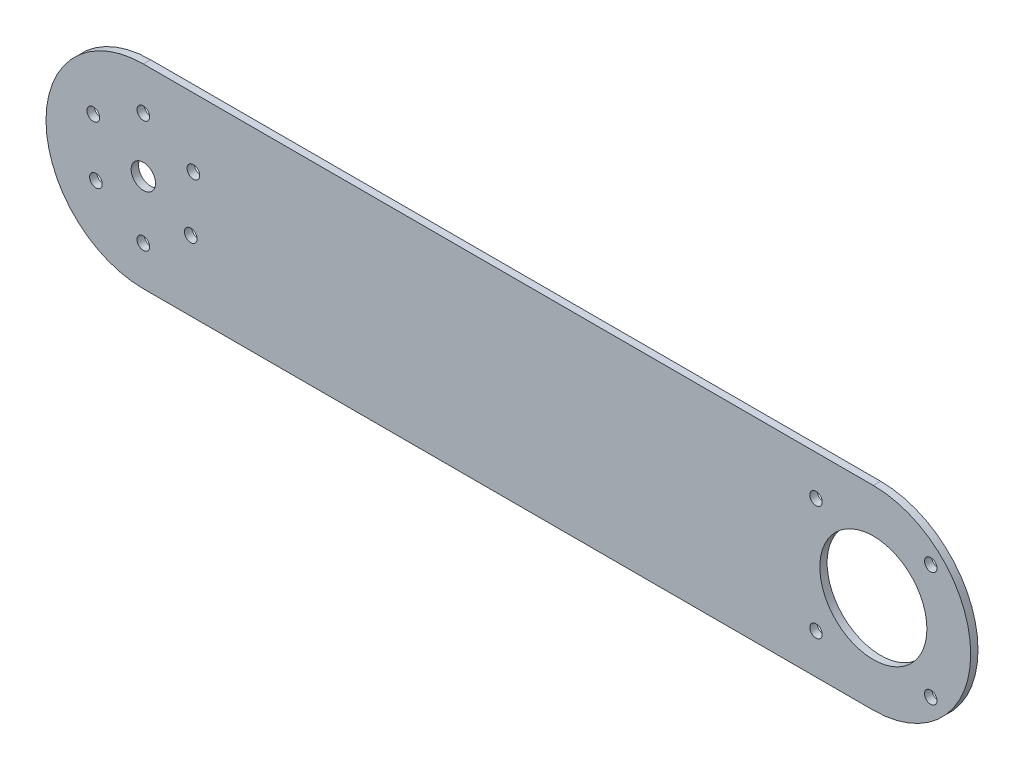
SolidWorks part; units mm, degrees
ref_plane "前视基准面" through (0, 0, 0) normal (0, 0, 1) x (1, 0, 0)
ref_plane "上视基准面" through (0, 0, 0) normal (0, 1, 0) x (1, 0, 0)
ref_plane "右视基准面" through (0, 0, 0) normal (1, 0, 0) x (0, 0, -1)
sketch "草图1" plane through (0, 0, 0) normal (0, 0, 1) x (1, 0, 0)
  line L0 (-3.8235, 4.644) -> (296.1765, 4.644) construction
  line L1 (-3.8235, 4.644) -> (35.4488, -18.03) construction
  line L3 (-3.8235, 44.644) -> (296.1765, 44.644)
  line L4 (-3.8235, -35.356) -> (296.1765, -35.356)
  line L5 (272.6065, 28.214) -> (319.7465, 28.214) construction
  line L6 (272.6065, 28.214) -> (272.6065, -18.926) construction
  line L7 (272.6065, -18.926) -> (319.7465, -18.926) construction
  line L8 (319.7465, 28.214) -> (319.7465, -18.926) construction
  line L9 (272.6065, 28.214) -> (319.7465, -18.926) construction
  line L10 (272.6065, -18.926) -> (319.7465, 28.214) construction
  circle A0 centre (-3.8235, 4.644) radius 23.75 construction
  circle A1 centre (-3.8235, 4.644) radius 22.5 construction
  circle A2 centre (-3.8235, -19.106) radius 2.6
  circle A5 centre (15.662, -6.606) radius 2.6
  circle A16 centre (-3.8235, 4.644) radius 40 construction
  circle A17 centre (296.1765, 4.644) radius 40 construction
  arc A18 (-3.8235, 44.644) -> (-3.8235, -35.356) centre (-3.8235, 4.644) ccw
  arc A19 (296.1765, 44.644) -> (296.1765, -35.356) centre (296.1765, 4.644) cw
  circle A20 centre (-3.8235, 4.644) radius 5
  circle A24 centre (296.1765, 4.644) radius 22
  circle A25 centre (272.6065, 28.214) radius 2.55
  circle A26 centre (319.7465, 28.214) radius 2.55
  circle A27 centre (319.7465, -18.926) radius 2.55
  circle A28 centre (272.6065, -18.926) radius 2.55
  circle A29 centre (-24.3917, 16.519) radius 2.6
  circle A30 centre (16.7446, 16.519) radius 2.6
  circle A31 centre (-23.3091, -6.606) radius 2.6
  circle A32 centre (-3.8235, 27.144) radius 2.6
  dimension "D1" = 47.5
  dimension "D2" = 45
  dimension "D3" = 5.2
  dimension "D5" = 5.2
  dimension "D6" = 300
  dimension "D7" = 47.14
  dimension "D8" = 40
  dimension "D9" = 5.1
  dimension "D10" = 4
  dimension "D11" = 44
  dimension "D4" = 30
  dimension "D12" = 3
  dimension "D13" = 3
extrude "凸台-拉伸1" add sketch "草图1" along normal blind 3 contours L3 A19 L4 A18
